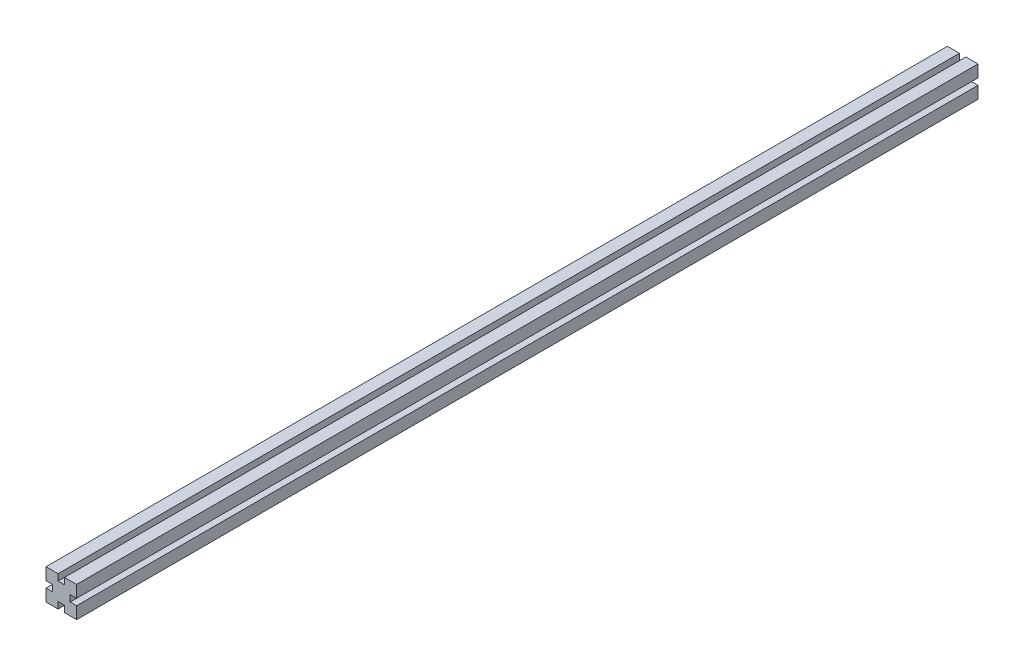
SolidWorks part; units mm, degrees
ref_plane "Front Plane" through (0, 0, 0) normal (0, 0, 1) x (1, 0, 0)
ref_plane "Top Plane" through (0, 0, 0) normal (0, 1, 0) x (1, 0, 0)
ref_plane "Right Plane" through (0, 0, 0) normal (1, 0, 0) x (0, 0, -1)
sketch "Sketch1" plane through (0, 0, 0) normal (0, 0, 1) x (1, 0, 0)
  line L0 (-19.05, -19.05) -> (-4, -19.05)
  line L1 (-4, -19.05) -> (-4, -11.05)
  line L2 (-4, -11.05) -> (4, -11.05)
  line L3 (4, -11.05) -> (4, -19.05)
  line L4 (4, -19.05) -> (19.05, -19.05)
  line L5 (19.05, -19.05) -> (19.05, -4)
  line L6 (19.05, -4) -> (11.05, -4)
  line L7 (11.05, -4) -> (11.05, 4)
  line L8 (11.05, 4) -> (19.05, 4)
  line L9 (19.05, 4) -> (19.05, 19.05)
  line L10 (19.05, 19.05) -> (4, 19.05)
  line L11 (4, 19.05) -> (4, 11.05)
  line L12 (4, 11.05) -> (-4, 11.05)
  line L13 (-4, 11.05) -> (-4, 19.05)
  line L14 (-4, 19.05) -> (-19.05, 19.05)
  line L15 (-19.05, 19.05) -> (-19.05, 4)
  line L16 (-19.05, 4) -> (-11.05, 4)
  line L17 (-11.05, 4) -> (-11.05, -4)
  line L18 (-11.05, -4) -> (-19.05, -4)
  line L19 (-19.05, -4) -> (-19.05, -19.05)
extrude "Profile" add sketch "Sketch1" along normal blind 1122
equation "\"length\" = 1122.0mm"
equation "\"D1@Profile\" = \"length\""
